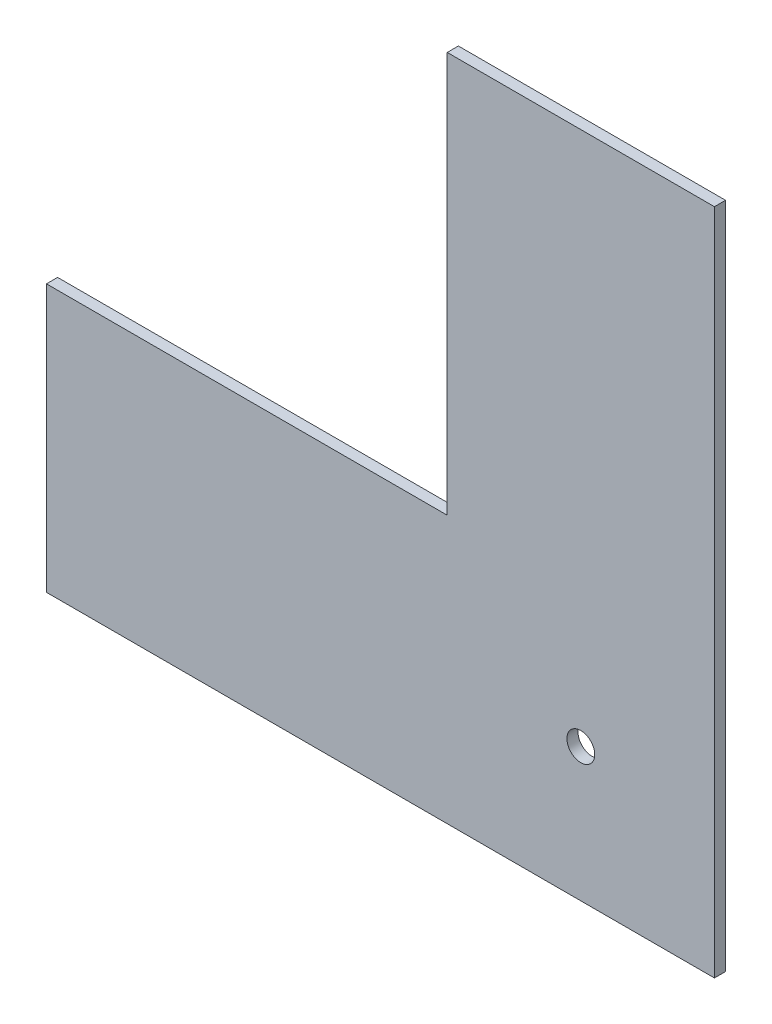
SolidWorks part; units mm, degrees
ref_plane "前视基准面" through (0, 0, 0) normal (0, 0, 1) x (1, 0, 0)
ref_plane "上视基准面" through (0, 0, 0) normal (0, 1, 0) x (1, 0, 0)
ref_plane "右视基准面" through (0, 0, 0) normal (1, 0, 0) x (0, 0, -1)
sketch "草图1" plane through (0, 0, 0) normal (0, 0, 1) x (1, 0, 0)
  line L0 (-14.9091, 0) -> (21.0909, 0)
  line L1 (21.0909, 36) -> (21.0909, 0)
  line L2 (21.0909, 36) -> (45.0909, 36)
  line L3 (45.0909, 36) -> (45.0909, -24)
  line L4 (45.0909, -24) -> (-14.9091, -24)
  line L5 (-14.9091, -24) -> (-14.9091, 0)
  dimension "D1" = 24
  dimension "D2" = 24
  dimension "D3" = 60
  dimension "D4" = 60
extrude "凸台-拉伸1" add sketch "草图1" along normal blind 1
sketch "草图2" plane through (0, 0, 1) normal (0, 0, 1) x (1, 0, 0)
  line L0 (21.0909, 0) -> (45.0909, -24) construction
  circle A0 centre (33.0909, -12) radius 1.7979 construction
hole_wizard "M3 螺纹孔的螺纹孔钻头1" positions "3D草图1" profile "草图3" hole size "M3" standard "GB" end condition through all
sketch3d "3D草图1"
  point P0 (33.0909, -12, 1)
sketch "草图3" plane through (33.0909, -12, 1) normal (1, 0, 0) x (0, -1, 0)
  line L0 (0, 0) -> (0, 1)
  line L1 (0, 1) -> (1.25, 1)
  line L2 (1.25, 1) -> (1.25, 0)
  line L5 (1.25, 0) -> (0, 0)
  line L11 (0, -6.35) -> (0, 107.95) construction
  dimension "通孔孔直径" = 2.5
  dimension "通孔孔深度" = 1
